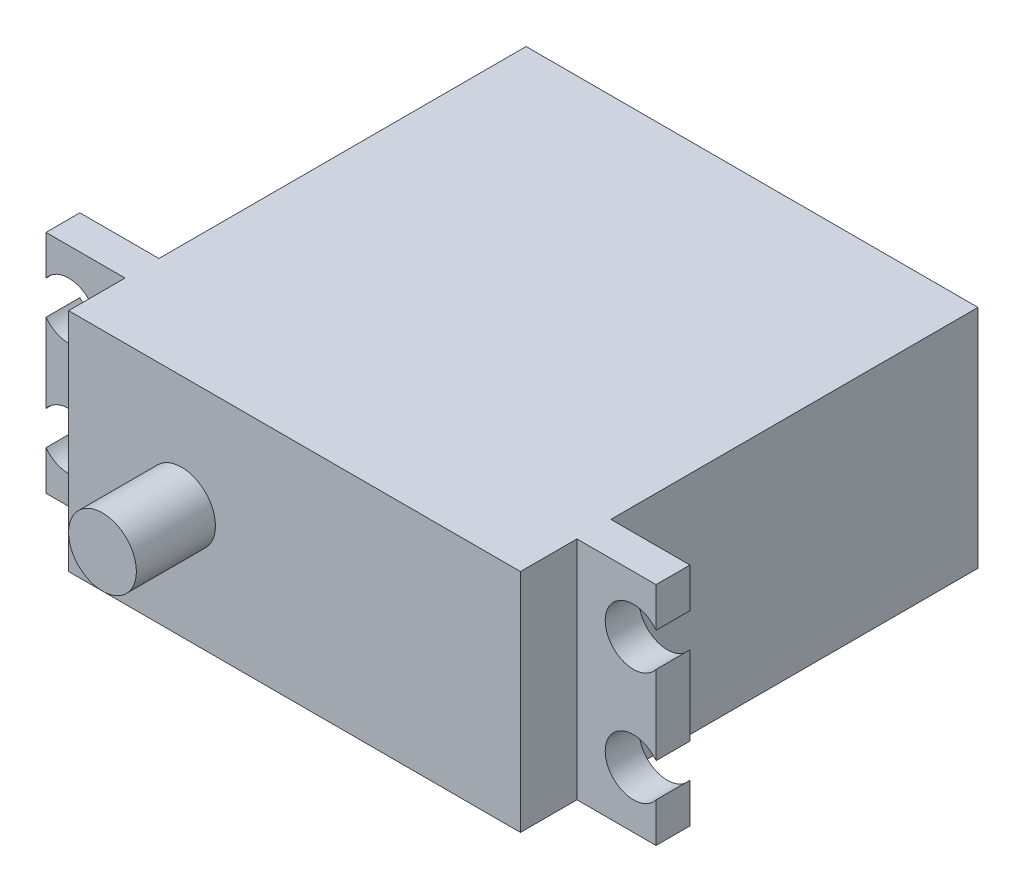
SolidWorks part; units mm, degrees
ref_plane "前视基准面" through (0, 0, 0) normal (0, 0, 1) x (1, 0, 0)
ref_plane "上视基准面" through (0, 0, 0) normal (0, 1, 0) x (1, 0, 0)
ref_plane "右视基准面" through (0, 0, 0) normal (1, 0, 0) x (0, 0, -1)
sketch "草图1" plane through (0, 0, 0) normal (0, 0, 1) x (1, 0, 0)
  line L1 (0, 0) -> (40, 0)
  line L2 (0, 0) -> (0, -20)
  line L3 (0, -20) -> (40, -20)
  line L4 (40, 0) -> (40, -20)
  dimension "D1" = 40
  dimension "D2" = 20
extrude "凸台-拉伸1" add sketch "草图1" along normal blind 40.5
sketch "草图2" plane through (0, 0, 40.5) normal (0, 0, 1) x (1, 0, 0)
  line L0 (40, 0) -> (0, 0) construction
  line L1 (0, 0) -> (0, -20) construction
  circle A0 centre (10, -10) radius 3
  dimension "D1" = 6
  dimension "D2" = 10
  dimension "D3" = 10
extrude "凸台-拉伸2" add sketch "草图2" along normal blind 7
sketch "草图3" plane through (0, 0, 40.5) normal (0, 0, 1) x (1, 0, 0)
  line L0 (0, 0) -> (0, -20) construction
  line L1 (40, 0) -> (47, 0)
  line L2 (40, 0) -> (40, -20)
  line L3 (40, -20) -> (47, -20)
  line L4 (47, 0) -> (47, -20)
  line L5 (0, -20) -> (-7, -20)
  line L6 (0, -20) -> (0, 0)
  line L7 (0, 0) -> (-7, 0)
  line L8 (-7, -20) -> (-7, 0)
  dimension "D1" = 7
  dimension "D2" = 7
  dimension "D3" = 20
  dimension "D4" = 20
extrude "凸台-拉伸3" add sketch "草图3" against normal blind 3 from offset 5 offset against normal yes
sketch "草图4" plane through (0, 0, 35.5) normal (0, 0, 1) x (1, 0, 0)
  line L0 (-5, -5) -> (45, -5) construction
  line L1 (45, -5) -> (45, -15) construction
  line L2 (-7, -10) -> (50.0229, -10) construction
  line L3 (-7, 0) -> (-7, -20) construction
  line L4 (20, 0) -> (20, -21.191) construction
  line L5 (40, 0) -> (0, 0) construction
  circle A0 centre (-5, -5) radius 2.5
  circle A1 centre (45, -5) radius 2.5
  circle A2 centre (-5, -15) radius 2.5
  circle A3 centre (45, -15) radius 2.5
  dimension "D3" = 5
  dimension "D4" = 5
  dimension "D5" = 5
  dimension "D6" = 5
  dimension "D1" = 50
  dimension "D2" = 10
extrude "切除-拉伸1" cut sketch "草图4" against normal blind 10
